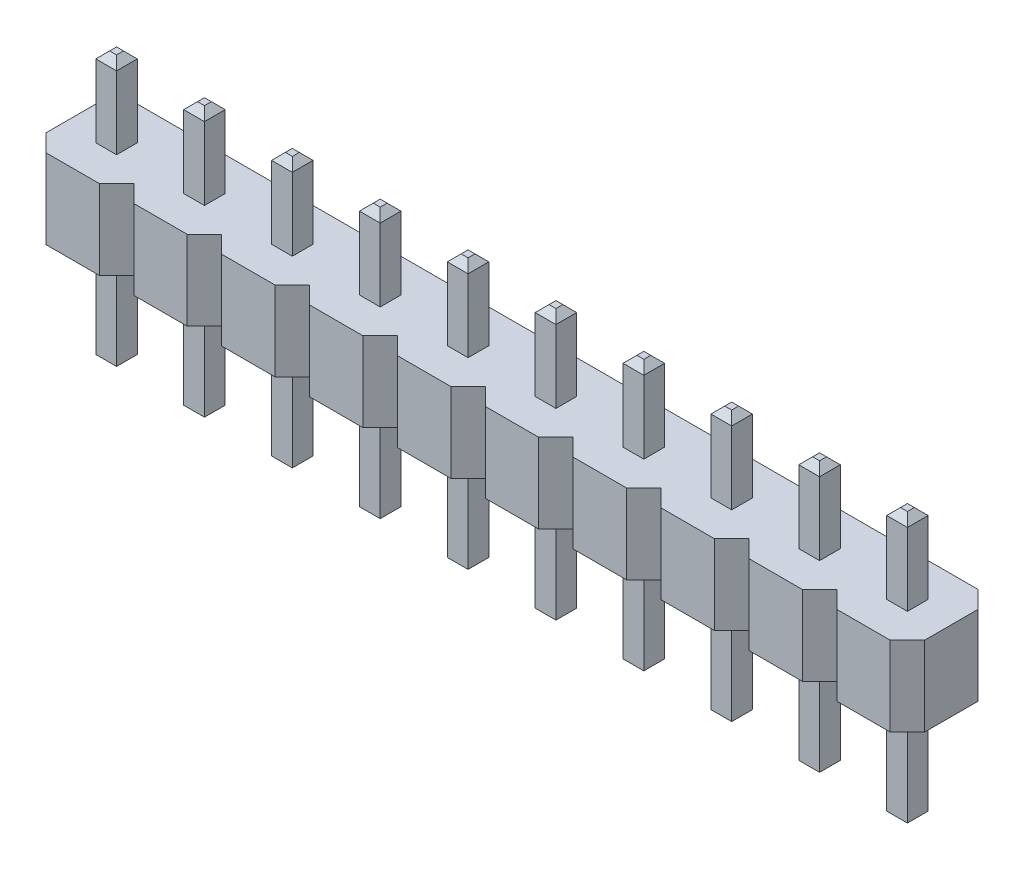
SolidWorks part; units mm, degrees
ref_plane "Front Plane" through (0, 0, 0) normal (0, 0, 1) x (1, 0, 0)
ref_plane "Top Plane" through (0, 0, 0) normal (0, 1, 0) x (1, 0, 0)
ref_plane "Right Plane" through (0, 0, 0) normal (1, 0, 0) x (0, 0, -1)
sketch "Sketch2" plane through (0, 0, 0) normal (0, 1, 0) x (1, 0, 0)
  line L0 (-1.27, 0.77) -> (-0.77, 1.27)
  line L1 (-0.77, -1.27) -> (0.77, -1.27)
  line L2 (-1.27, -0.77) -> (-1.27, 0.77)
  line L3 (-0.77, 1.27) -> (0.77, 1.27)
  line L4 (1.27, -0.77) -> (1.27, 0.77)
  line L5 (-1.27, -1.27) -> (1.27, 1.27) construction
  line L6 (-1.27, 1.27) -> (1.27, -1.27) construction
  line L7 (0.77, 1.27) -> (1.27, 0.77)
  line L8 (0.77, -1.27) -> (1.27, -0.77)
  line L9 (-1.27, -0.77) -> (-0.77, -1.27)
  line L10 (1.77, 1.27) -> (3.31, 1.27)
  line L11 (1.27, 0.77) -> (1.77, 1.27)
  line L12 (1.27, -0.77) -> (1.27, 0.77)
  line L13 (1.27, -0.77) -> (1.77, -1.27)
  line L14 (1.77, -1.27) -> (3.31, -1.27)
  line L15 (3.31, -1.27) -> (3.81, -0.77)
  line L16 (3.81, -0.77) -> (3.81, 0.77)
  line L17 (3.31, 1.27) -> (3.81, 0.77)
  line L18 (4.31, 1.27) -> (5.85, 1.27)
  line L19 (3.81, 0.77) -> (4.31, 1.27)
  line L20 (3.81, -0.77) -> (3.81, 0.77)
  line L21 (3.81, -0.77) -> (4.31, -1.27)
  line L22 (4.31, -1.27) -> (5.85, -1.27)
  line L23 (5.85, -1.27) -> (6.35, -0.77)
  line L24 (6.35, -0.77) -> (6.35, 0.77)
  line L25 (5.85, 1.27) -> (6.35, 0.77)
  line L26 (6.85, 1.27) -> (8.39, 1.27)
  line L27 (6.35, 0.77) -> (6.85, 1.27)
  line L28 (6.35, -0.77) -> (6.35, 0.77)
  line L29 (6.35, -0.77) -> (6.85, -1.27)
  line L30 (6.85, -1.27) -> (8.39, -1.27)
  line L31 (8.39, -1.27) -> (8.89, -0.77)
  line L32 (8.89, -0.77) -> (8.89, 0.77)
  line L33 (8.39, 1.27) -> (8.89, 0.77)
  line L34 (9.39, 1.27) -> (10.93, 1.27)
  line L35 (8.89, 0.77) -> (9.39, 1.27)
  line L36 (8.89, -0.77) -> (8.89, 0.77)
  line L37 (8.89, -0.77) -> (9.39, -1.27)
  line L38 (9.39, -1.27) -> (10.93, -1.27)
  line L39 (10.93, -1.27) -> (11.43, -0.77)
  line L40 (11.43, -0.77) -> (11.43, 0.77)
  line L41 (10.93, 1.27) -> (11.43, 0.77)
  line L42 (11.93, 1.27) -> (13.47, 1.27)
  line L43 (11.43, 0.77) -> (11.93, 1.27)
  line L44 (11.43, -0.77) -> (11.43, 0.77)
  line L45 (11.43, -0.77) -> (11.93, -1.27)
  line L46 (11.93, -1.27) -> (13.47, -1.27)
  line L47 (13.47, -1.27) -> (13.97, -0.77)
  line L48 (13.97, -0.77) -> (13.97, 0.77)
  line L49 (13.47, 1.27) -> (13.97, 0.77)
  line L50 (14.47, 1.27) -> (16.01, 1.27)
  line L51 (13.97, 0.77) -> (14.47, 1.27)
  line L52 (13.97, -0.77) -> (13.97, 0.77)
  line L53 (13.97, -0.77) -> (14.47, -1.27)
  line L54 (14.47, -1.27) -> (16.01, -1.27)
  line L55 (16.01, -1.27) -> (16.51, -0.77)
  line L56 (16.51, -0.77) -> (16.51, 0.77)
  line L57 (16.01, 1.27) -> (16.51, 0.77)
  line L58 (17.01, 1.27) -> (18.55, 1.27)
  line L59 (16.51, 0.77) -> (17.01, 1.27)
  line L60 (16.51, -0.77) -> (16.51, 0.77)
  line L61 (16.51, -0.77) -> (17.01, -1.27)
  line L62 (17.01, -1.27) -> (18.55, -1.27)
  line L63 (18.55, -1.27) -> (19.05, -0.77)
  line L64 (19.05, -0.77) -> (19.05, 0.77)
  line L65 (18.55, 1.27) -> (19.05, 0.77)
  line L66 (19.55, 1.27) -> (21.09, 1.27)
  line L67 (19.05, 0.77) -> (19.55, 1.27)
  line L68 (19.05, -0.77) -> (19.05, 0.77)
  line L69 (19.05, -0.77) -> (19.55, -1.27)
  line L70 (19.55, -1.27) -> (21.09, -1.27)
  line L71 (21.09, -1.27) -> (21.59, -0.77)
  line L72 (21.59, -0.77) -> (21.59, 0.77)
  line L73 (21.09, 1.27) -> (21.59, 0.77)
  line L74 (22.09, 1.27) -> (23.63, 1.27)
  line L75 (21.59, 0.77) -> (22.09, 1.27)
  line L76 (21.59, -0.77) -> (21.59, 0.77)
  line L77 (21.59, -0.77) -> (22.09, -1.27)
  line L78 (22.09, -1.27) -> (23.63, -1.27)
  line L79 (23.63, -1.27) -> (24.13, -0.77)
  line L80 (24.13, -0.77) -> (24.13, 0.77)
  line L81 (23.63, 1.27) -> (24.13, 0.77)
  point P0 (0, 0)
  dimension "D1" = 2.54
  dimension "D2" = 2.54
  dimension "D3" = 10
extrude "Boss-Extrude1" add sketch "Sketch2" along normal blind 2.3 contours L2 L9 L1 L8 L4 L7 L3 L0 | L17 L10 L11 L4 L13 L14 L15 L16 | L25 L18 L19 L16 L21 L22 L23 L24 | L33 L26 L27 L24 L29 L30 L31 L32 | L41 L34 L35 L32 L37 L38 L39 L40 | L49 L42 L43 L40 L45 L46 L47 L48 | L57 L50 L51 L48 L53 L54 L55 L56 | L65 L58 L59 L56 L61 L62 L63 L64 | L73 L66 L67 L64 L69 L70 L71 L72 | L81 L74 L75 L72 L77 L78 L79 L80
sketch "Sketch3" plane through (0, 2.3, 0) normal (0, 1, 0) x (1, 0, 0)
  line L0 (2.24, -0.3) -> (2.24, 0.3)
  line L1 (-0.3, -0.3) -> (0.3, -0.3)
  line L2 (-0.3, -0.3) -> (-0.3, 0.3)
  line L3 (-0.3, 0.3) -> (0.3, 0.3)
  line L4 (0.3, -0.3) -> (0.3, 0.3)
  line L5 (-0.3, -0.3) -> (0.3, 0.3) construction
  line L6 (-0.3, 0.3) -> (0.3, -0.3) construction
  line L7 (2.24, 0.3) -> (2.84, 0.3)
  line L8 (2.84, -0.3) -> (2.84, 0.3)
  line L9 (2.24, -0.3) -> (2.84, -0.3)
  line L10 (4.78, -0.3) -> (4.78, 0.3)
  line L11 (4.78, 0.3) -> (5.38, 0.3)
  line L12 (5.38, -0.3) -> (5.38, 0.3)
  line L13 (4.78, -0.3) -> (5.38, -0.3)
  line L14 (7.32, -0.3) -> (7.32, 0.3)
  line L15 (7.32, 0.3) -> (7.92, 0.3)
  line L16 (7.92, -0.3) -> (7.92, 0.3)
  line L17 (7.32, -0.3) -> (7.92, -0.3)
  line L18 (9.86, -0.3) -> (9.86, 0.3)
  line L19 (9.86, 0.3) -> (10.46, 0.3)
  line L20 (10.46, -0.3) -> (10.46, 0.3)
  line L21 (9.86, -0.3) -> (10.46, -0.3)
  line L22 (12.4, -0.3) -> (12.4, 0.3)
  line L23 (12.4, 0.3) -> (13, 0.3)
  line L24 (13, -0.3) -> (13, 0.3)
  line L25 (12.4, -0.3) -> (13, -0.3)
  line L26 (14.94, -0.3) -> (14.94, 0.3)
  line L27 (14.94, 0.3) -> (15.54, 0.3)
  line L28 (15.54, -0.3) -> (15.54, 0.3)
  line L29 (14.94, -0.3) -> (15.54, -0.3)
  line L30 (17.48, -0.3) -> (17.48, 0.3)
  line L31 (17.48, 0.3) -> (18.08, 0.3)
  line L32 (18.08, -0.3) -> (18.08, 0.3)
  line L33 (17.48, -0.3) -> (18.08, -0.3)
  line L34 (20.02, -0.3) -> (20.02, 0.3)
  line L35 (20.02, 0.3) -> (20.62, 0.3)
  line L36 (20.62, -0.3) -> (20.62, 0.3)
  line L37 (20.02, -0.3) -> (20.62, -0.3)
  line L38 (22.56, -0.3) -> (22.56, 0.3)
  line L39 (22.56, 0.3) -> (23.16, 0.3)
  line L40 (23.16, -0.3) -> (23.16, 0.3)
  line L41 (22.56, -0.3) -> (23.16, -0.3)
  point P0 (0, 0)
  dimension "D1" = 0.6
  dimension "D2" = 0.6
  dimension "D3" = 10
extrude "Boss-Extrude2" add sketch "Sketch3" along normal blind 2.3 and the other way blind 5.5 contours L1 L4 L3 L2 | L0 L9 L8 L7 | L10 L13 L12 L11 | L14 L17 L16 L15 | L18 L21 L20 L19 | L22 L25 L24 L23 | L26 L29 L28 L27 | L30 L33 L32 L31 | L34 L37 L36 L35 | L38 L41 L40 L39
chamfer "Chamfer1" distance 0.2 angle 45 80 edges at (22.86, -3.2, 0.3) (23.16, -3.2, 0) (22.86, -3.2, -0.3) (22.56, -3.2, 0) (20.32, -3.2, 0.3) (20.62, -3.2, 0) (20.32, -3.2, -0.3) (20.02, -3.2, 0) (17.78, -3.2, 0.3) (18.08, -3.2, 0) (17.78, -3.2, -0.3) (17.48, -3.2, 0) (15.24, -3.2, 0.3) (15.54, -3.2, 0) (15.24, -3.2, -0.3) (14.94, -3.2, 0) (12.7, -3.2, 0.3) (13, -3.2, 0) (12.7, -3.2, -0.3) (12.4, -3.2, 0) (10.16, -3.2, 0.3) (10.46, -3.2, 0) (10.16, -3.2, -0.3) (9.86, -3.2, 0) (7.62, -3.2, 0.3) (7.92, -3.2, 0) (7.62, -3.2, -0.3) (7.32, -3.2, 0) (5.08, -3.2, 0.3) (5.38, -3.2, 0) (5.08, -3.2, -0.3) (4.78, -3.2, 0) (2.54, -3.2, 0.3) (2.84, -3.2, 0) (2.54, -3.2, -0.3) (2.24, -3.2, 0) (0.3, -3.2, 0) (0, -3.2, -0.3) (-0.3, -3.2, 0) (0, -3.2, 0.3) (22.86, 4.6, -0.3) (23.16, 4.6, 0) (22.86, 4.6, 0.3) (22.56, 4.6, 0) (20.32, 4.6, -0.3) (20.62, 4.6, 0) (20.32, 4.6, 0.3) (20.02, 4.6, 0) (17.78, 4.6, -0.3) (18.08, 4.6, 0) (17.78, 4.6, 0.3) (17.48, 4.6, 0) (15.24, 4.6, -0.3) (15.54, 4.6, 0) (15.24, 4.6, 0.3) (14.94, 4.6, 0) (12.7, 4.6, -0.3) (13, 4.6, 0) (12.7, 4.6, 0.3) (12.4, 4.6, 0) (10.16, 4.6, -0.3) (10.46, 4.6, 0) (10.16, 4.6, 0.3) (9.86, 4.6, 0) (2.54, 4.6, -0.3) (2.84, 4.6, 0) (2.54, 4.6, 0.3) (2.24, 4.6, 0) (7.62, 4.6, -0.3) (7.92, 4.6, 0) (7.62, 4.6, 0.3) (7.32, 4.6, 0) (5.08, 4.6, -0.3) (5.38, 4.6, 0) (5.08, 4.6, 0.3) (4.78, 4.6, 0) (-0.3, 4.6, 0) (0, 4.6, -0.3) (0.3, 4.6, 0) (0, 4.6, 0.3)
